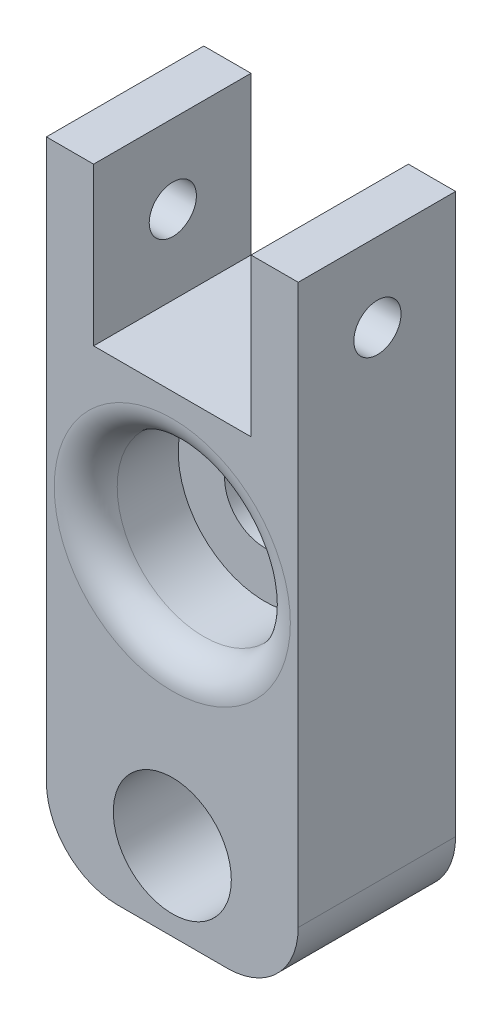
SolidWorks part; units mm, degrees
ref_plane "Front Plane" through (0, 0, 0) normal (0, 0, 1) x (1, 0, 0)
ref_plane "Top Plane" through (0, 0, 0) normal (0, 1, 0) x (1, 0, 0)
ref_plane "Right Plane" through (0, 0, 0) normal (1, 0, 0) x (0, 0, -1)
sketch "Sketch1" plane through (0, 0, 0) normal (0, 0, 1) x (1, 0, 0)
  line L0 (-16, -340) -> (16, -340)
  line L1 (16, -340) -> (16, -400)
  line L2 (210, -400) -> (-210, -400) construction
  line L3 (16, -400) -> (-16, -400)
  line L4 (-16, -400) -> (-16, -340)
  line L5 (-10, -340) -> (-10, 0) construction
  line L7 (10, -340) -> (10, 0) construction
  dimension "D1" = 6
  dimension "D2" = 6
extrude "Boss-Extrude1" add sketch "Sketch1" against normal blind 20
sketch "Sketch2" plane through (0, 0, 0) normal (0, 0, 1) x (1, 0, 0)
  circle A0 centre (0, -390) radius 7.5
  circle A2 centre (0, -358) radius 5.1
  dimension "D1" = 15
  dimension "D2" = 10.2
extrude "Cut-Extrude1" cut sketch "Sketch2" against normal through all
sketch "Sketch3" plane through (0, 0, 0) normal (0, 0, 1) x (1, 0, 0)
  circle A0 centre (0, -358) radius 11
  dimension "D1" = 22
extrude "Cut-Extrude2" cut sketch "Sketch3" against normal blind 11.75
sketch "Sketch4" plane through (0, -340, 0) normal (0, 1, 0) x (1, 0, 0)
  line L0 (16, 20) -> (10, 20)
  line L1 (16, 20) -> (-16, 20) construction
  line L3 (10, 20) -> (10, 0)
  line L4 (16, 0) -> (-16, 0) construction
  line L5 (10, 0) -> (16, 0)
  line L6 (16, 0) -> (16, 20)
  line L7 (-16, 20) -> (-10, 20)
  line L8 (-10, 20) -> (-10, 0)
  line L9 (-10, 0) -> (-16, 0)
  line L10 (-16, 0) -> (-16, 20)
  dimension "D1" = 6
  dimension "D2" = 6
extrude "Boss-Extrude2" add sketch "Sketch4" along normal blind 20
sketch "Sketch5" plane through (-16, 0, 0) normal (-1, 0, 0) x (0, 0, 1)
  line L0 (-20, -320) -> (0, -320) construction
  circle A0 centre (-10.0658, -330) radius 3
  dimension "D2" = 6
  dimension "D1" = 10
extrude "Cut-Extrude3" cut sketch "Sketch5" against normal through all
fillet "Fillet2" radius 9 2 edges at (16, -400, -10) (-16, -400, -10)
fillet "Fillet3" radius 4 1 edges at (11, -358, 0)
